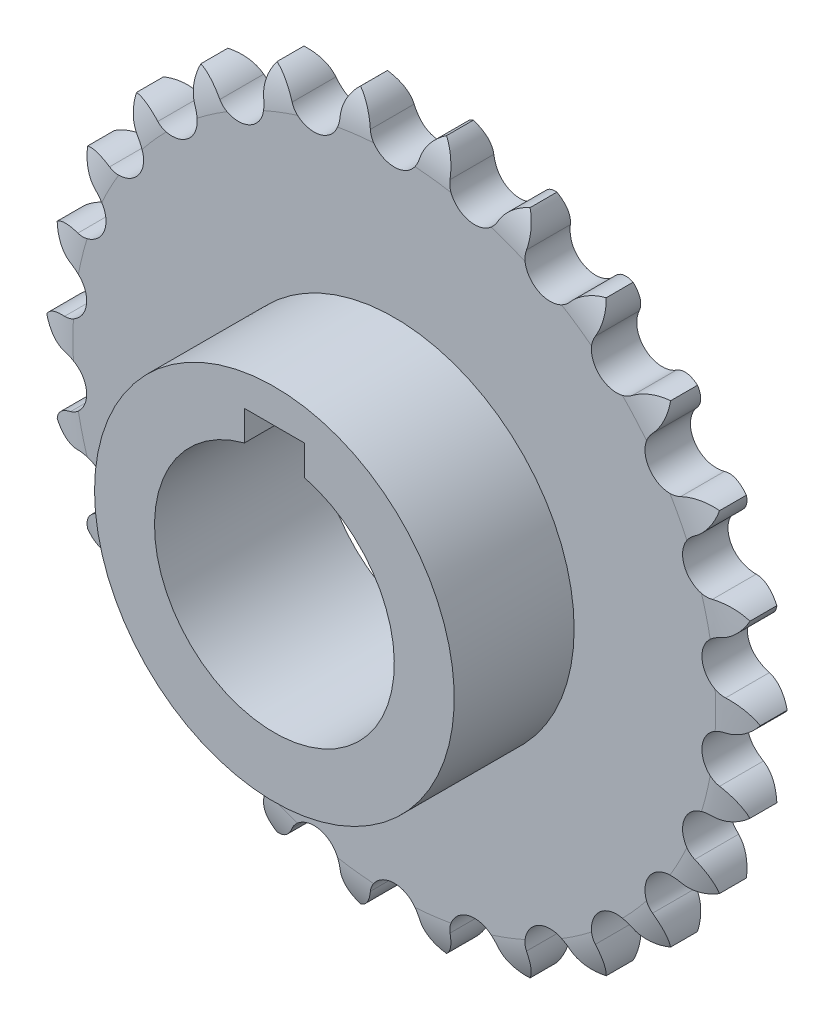
SolidWorks part; units mm, degrees
ref_plane "Front Plane" through (0, 0, 0) normal (0, 0, 1) x (1, 0, 0)
ref_plane "Top Plane" through (0, 0, 0) normal (0, 1, 0) x (1, 0, 0)
ref_plane "Right Plane" through (0, 0, 0) normal (1, 0, 0) x (0, 0, -1)
sketch "Sketch2" plane through (0, 0, 0) normal (0, 0, 1) x (1, 0, 0)
  line L0 (0, 0) -> (0, 37.2084) construction
  line L1 (0, 0) -> (6.3134, 33.5613) construction
  circle A6 centre (0, 0) radius 37.2084 construction
  circle A7 centre (0, 0) radius 34.9665 construction
  circle A8 centre (0, 0) radius 34.15 construction
  arc A9 (-2.5786, 34.3926) -> (2.5786, 34.3926) centre (0, 34.9665) ccw
  arc A10 (4.5071, 36.9344) -> (2.5786, 34.3926) centre (6.3134, 33.5613) ccw
  arc A11 (-4.5071, 36.9344) -> (-2.5786, 34.3926) centre (-6.3134, 33.5613) cw
  arc A12 (4.4629, 36.9397) -> (5.7271, 34.0103) centre (1.9018, 34.097) cw
  arc A13 (5.7271, 34.0103) -> (10.7343, 32.7761) centre (8.368, 33.9504) ccw
  arc A14 (13.2151, 34.7825) -> (10.7343, 32.7761) centre (14.1617, 31.0752) ccw
  arc A15 (13.1735, 34.7983) -> (13.6998, 31.6514) centre (10.0064, 32.6511) cw
  arc A16 (13.6998, 31.6514) -> (18.2662, 29.2548) centre (16.2497, 30.9613) ccw
  arc A17 (21.1551, 30.6092) -> (18.2662, 29.2548) centre (21.187, 26.7831) ccw
  arc A18 (21.1184, 30.6345) -> (20.8764, 27.4531) centre (17.5296, 29.3076) cw
  arc A19 (20.8764, 27.4531) -> (24.7366, 24.0333) centre (23.1871, 26.1728) ccw
  arc A20 (27.8656, 24.657) -> (24.7366, 24.0333) centre (26.981, 20.9344) ccw
  arc A21 (27.8361, 24.6904) -> (26.8398, 21.6593) centre (24.034, 24.2609) cw
  arc A22 (26.8398, 21.6593) -> (29.7693, 17.4151) centre (28.7769, 19.8632) ccw
  arc A23 (32.9567, 17.2719) -> (29.7693, 17.4151) centre (31.2069, 13.8691) ccw
  arc A24 (32.936, 17.3113) -> (31.2433, 14.6068) centre (29.1416, 17.8042) cw
  arc A25 (31.2433, 14.6068) -> (33.072, 9.7848) centre (32.6942, 12.3993) ccw
  arc A26 (36.1325, 8.8829) -> (33.072, 9.7848) centre (33.6192, 5.9978) ccw
  arc A27 (36.1218, 8.9261) -> (33.831, 6.7053) centre (32.5556, 10.3128) cw
  arc A28 (33.831, 6.7053) -> (34.4526, 1.5858) centre (34.7116, 4.2147) ccw
  arc A29 (37.2083, -0.0223) -> (34.4526, 1.5858) centre (34.0776, -2.222) ccw
  arc A30 (37.2083, 0.0223) -> (34.4526, -1.5858) centre (34.0776, 2.222) cw
  arc A31 (34.4526, -1.5858) -> (33.831, -6.7053) centre (34.7116, -4.2147) ccw
  arc A32 (36.1218, -8.9261) -> (33.831, -6.7053) centre (32.5556, -10.3128) ccw
  arc A33 (36.1325, -8.8829) -> (33.072, -9.7848) centre (33.6192, -5.9978) cw
  arc A34 (33.072, -9.7848) -> (31.2433, -14.6068) centre (32.6942, -12.3993) ccw
  arc A35 (32.936, -17.3113) -> (31.2433, -14.6068) centre (29.1416, -17.8042) ccw
  arc A36 (32.9567, -17.2719) -> (29.7693, -17.4151) centre (31.2069, -13.8691) cw
  arc A37 (29.7693, -17.4151) -> (26.8398, -21.6593) centre (28.7769, -19.8632) ccw
  arc A38 (27.8361, -24.6904) -> (26.8398, -21.6593) centre (24.034, -24.2609) ccw
  arc A39 (27.8656, -24.657) -> (24.7366, -24.0333) centre (26.981, -20.9344) cw
  arc A40 (24.7366, -24.0333) -> (20.8764, -27.4531) centre (23.1871, -26.1728) ccw
  arc A41 (21.1184, -30.6345) -> (20.8764, -27.4531) centre (17.5296, -29.3076) ccw
  arc A42 (21.1551, -30.6092) -> (18.2662, -29.2548) centre (21.187, -26.7831) cw
  arc A43 (18.2662, -29.2548) -> (13.6998, -31.6514) centre (16.2497, -30.9613) ccw
  arc A44 (13.1735, -34.7983) -> (13.6998, -31.6514) centre (10.0064, -32.6511) ccw
  arc A45 (13.2151, -34.7825) -> (10.7343, -32.7761) centre (14.1617, -31.0752) cw
  arc A46 (10.7343, -32.7761) -> (5.7271, -34.0103) centre (8.368, -33.9504) ccw
  arc A47 (4.4629, -36.9397) -> (5.7271, -34.0103) centre (1.9018, -34.097) ccw
  arc A48 (4.5071, -36.9344) -> (2.5786, -34.3926) centre (6.3134, -33.5613) cw
  arc A49 (2.5786, -34.3926) -> (-2.5786, -34.3926) centre (0, -34.9665) ccw
  arc A50 (-4.5071, -36.9344) -> (-2.5786, -34.3926) centre (-6.3134, -33.5613) ccw
  arc A51 (-4.4629, -36.9397) -> (-5.7271, -34.0103) centre (-1.9018, -34.097) cw
  arc A52 (-5.7271, -34.0103) -> (-10.7343, -32.7761) centre (-8.368, -33.9504) ccw
  arc A53 (-13.2151, -34.7825) -> (-10.7343, -32.7761) centre (-14.1617, -31.0752) ccw
  arc A54 (-13.1735, -34.7983) -> (-13.6998, -31.6514) centre (-10.0064, -32.6511) cw
  arc A55 (-13.6998, -31.6514) -> (-18.2662, -29.2548) centre (-16.2497, -30.9613) ccw
  arc A56 (-21.1551, -30.6092) -> (-18.2662, -29.2548) centre (-21.187, -26.7831) ccw
  arc A57 (-21.1184, -30.6345) -> (-20.8764, -27.4531) centre (-17.5296, -29.3076) cw
  arc A58 (-20.8764, -27.4531) -> (-24.7366, -24.0333) centre (-23.1871, -26.1728) ccw
  arc A59 (-27.8656, -24.657) -> (-24.7366, -24.0333) centre (-26.981, -20.9344) ccw
  arc A60 (-27.8361, -24.6904) -> (-26.8398, -21.6593) centre (-24.034, -24.2609) cw
  arc A61 (-26.8398, -21.6593) -> (-29.7693, -17.4151) centre (-28.7769, -19.8632) ccw
  arc A62 (-32.9567, -17.2719) -> (-29.7693, -17.4151) centre (-31.2069, -13.8691) ccw
  arc A63 (-32.936, -17.3113) -> (-31.2433, -14.6068) centre (-29.1416, -17.8042) cw
  arc A64 (-31.2433, -14.6068) -> (-33.072, -9.7848) centre (-32.6942, -12.3993) ccw
  arc A65 (-36.1325, -8.8829) -> (-33.072, -9.7848) centre (-33.6192, -5.9978) ccw
  arc A66 (-36.1218, -8.9261) -> (-33.831, -6.7053) centre (-32.5556, -10.3128) cw
  arc A67 (-33.831, -6.7053) -> (-34.4526, -1.5858) centre (-34.7116, -4.2147) ccw
  arc A68 (-37.2083, 0.0223) -> (-34.4526, -1.5858) centre (-34.0776, 2.222) ccw
  arc A69 (-37.2083, -0.0223) -> (-34.4526, 1.5858) centre (-34.0776, -2.222) cw
  arc A70 (-34.4526, 1.5858) -> (-33.831, 6.7053) centre (-34.7116, 4.2147) ccw
  arc A71 (-36.1218, 8.9261) -> (-33.831, 6.7053) centre (-32.5556, 10.3128) ccw
  arc A72 (-36.1325, 8.8829) -> (-33.072, 9.7848) centre (-33.6192, 5.9978) cw
  arc A73 (-33.072, 9.7848) -> (-31.2433, 14.6068) centre (-32.6942, 12.3993) ccw
  arc A74 (-32.936, 17.3113) -> (-31.2433, 14.6068) centre (-29.1416, 17.8042) ccw
  arc A75 (-32.9567, 17.2719) -> (-29.7693, 17.4151) centre (-31.2069, 13.8691) cw
  arc A76 (-29.7693, 17.4151) -> (-26.8398, 21.6593) centre (-28.7769, 19.8632) ccw
  arc A77 (-27.8361, 24.6904) -> (-26.8398, 21.6593) centre (-24.034, 24.2609) ccw
  arc A78 (-27.8656, 24.657) -> (-24.7366, 24.0333) centre (-26.981, 20.9344) cw
  arc A79 (-24.7366, 24.0333) -> (-20.8764, 27.4531) centre (-23.1871, 26.1728) ccw
  arc A80 (-21.1184, 30.6345) -> (-20.8764, 27.4531) centre (-17.5296, 29.3076) ccw
  arc A81 (-21.1551, 30.6092) -> (-18.2662, 29.2548) centre (-21.187, 26.7831) cw
  arc A82 (-18.2662, 29.2548) -> (-13.6998, 31.6514) centre (-16.2497, 30.9613) ccw
  arc A83 (-13.1735, 34.7983) -> (-13.6998, 31.6514) centre (-10.0064, 32.6511) ccw
  arc A84 (-13.2151, 34.7825) -> (-10.7343, 32.7761) centre (-14.1617, 31.0752) cw
  arc A85 (-10.7343, 32.7761) -> (-5.7271, 34.0103) centre (-8.368, 33.9504) ccw
  arc A86 (-4.4629, 36.9397) -> (-5.7271, 34.0103) centre (-1.9018, 34.097) ccw
  circle A87 centre (0, 0) radius 12.5
  point P192 (0, 0)
  dimension "D1" = 74.4167
  dimension "D2" = 69.933
  dimension "D3" = 68.3
  dimension "D4" = 7.6526
  dimension "D5" = 5.2833
  dimension "D6" = 26
extrude "Boss-Extrude1" add sketch "Sketch2" along normal blind 4.7333 contours A11 A86 A85 A84 A83 A82 A81 A80 A79 A78 A77 A76 A75 A74 A73 A72 A71 A70 A69 A68 A67 A66 A65 A64 A63 A62 A61 A60 A59 A58 A57 A56 A55 A54 A53 A52 A51 A50 A49 A48 A47 A46 A45 A44 A43 A42 A41 A40 A39 A38 A37
sketch "Sketch3" plane through (0, 0, 0) normal (1, 0, 0) x (0, 0, -1)
  line L0 (0, 0) -> (-68.5563, 0) construction
  line L1 (-1037.8905, 12.5) -> (48962.1095, 12.5) construction
  line L2 (-1045.1774, 18.75) -> (48954.8226, 18.75) construction
  line L3 (-4.7333, -976.8387) -> (-4.7333, 49023.1613) construction
  line L4 (-4.7333, 24.6632) -> (-4.7333, 21.6593) construction
  line L6 (-4.7333, 18.75) -> (-17.2333, 18.75)
  line L7 (-4.7333, 18.75) -> (-4.7333, 12.5)
  line L8 (-4.7333, 12.5) -> (-17.2333, 12.5)
  line L9 (-17.2333, 18.75) -> (-17.2333, 12.5)
  point P12 (-4.7333, 23.1613)
  dimension "D1" = 12.5
  dimension "D2" = 18.75
  dimension "D3" = 12.5
revolve "Revolve1" add sketch "Sketch3" angle 360 about L0
sketch "Sketch4" plane through (0, 0, 17.2333) normal (0, 0, 1) x (1, 0, 0)
  line L0 (0, 0) -> (0, 18.75) construction
  line L2 (-3.125, 12.1031) -> (3.125, 12.1031)
  line L3 (-3.125, 12.1031) -> (-3.125, 15.2281)
  line L4 (-3.125, 15.2281) -> (3.125, 15.2281)
  line L5 (3.125, 12.1031) -> (3.125, 15.2281)
  circle A0 centre (0, 0) radius 18.75 construction
  circle A1 centre (0, 0) radius 12.5 construction
  dimension "D1" = 6.25
  dimension "D2" = 3.125
extrude "Cut-Extrude1" cut sketch "Sketch4" against normal through all
sketch "Sketch5" plane through (0, 0, 0) normal (1, 0, 0) x (0, 0, -1)
  line L0 (-2.3666, -963.0786) -> (-2.3667, 49036.9214) construction
  line L1 (-4.7333, 36.9214) -> (0, 36.9214) construction
  line L2 (-3.6916, -963.9205) -> (-3.6916, 49036.0795) construction
  line L3 (-4.7333, 33.0833) -> (-5.486, 33.0833)
  line L4 (-4.7333, 34.7757) -> (-4.7333, 31.6514) construction
  line L5 (-5.486, 33.0833) -> (-5.486, 37.3333)
  line L6 (-5.486, 37.3333) -> (-3.6916, 37.3333)
  line L7 (-69.9604, 0) -> (49.3465, 0) construction
  line L8 (0, 33.0833) -> (0.7527, 33.0833)
  line L9 (0.7527, 33.0833) -> (0.7527, 37.3333)
  line L10 (0.7527, 37.3333) -> (-1.0417, 37.3333)
  arc A0 (-3.6916, 37.3333) -> (-4.7333, 33.0833) centre (3.5973, 33.2941) ccw
  arc A1 (-1.0417, 37.3333) -> (0, 33.0833) centre (-8.3306, 33.2941) cw
  point P5 (-2.3666, 36.9214)
  dimension "D2" = 8.3333
  dimension "D1" = 1.0417
  dimension "D3" = 33.0833
  dimension "D4" = 37.3333
revolve "Cut-Revolve1" cut sketch "Sketch5" angle 360 about L7
ref_plane "Plane2" through (0, 0, 2.3666) normal (0, 0, -1) x (-1, 0, 0)
